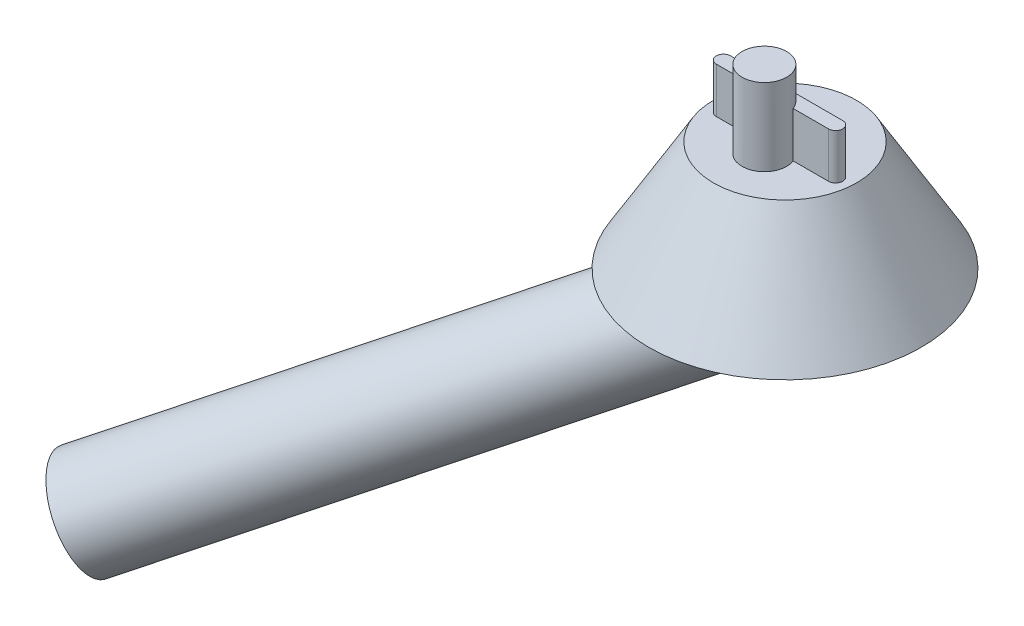
SolidWorks part; units mm, degrees
ref_plane "Front Plane" through (0, 0, 0) normal (0, 0, 1) x (1, 0, 0)
ref_plane "Top Plane" through (0, 0, 0) normal (0, 1, 0) x (1, 0, 0)
ref_plane "Right Plane" through (0, 0, 0) normal (1, 0, 0) x (0, 0, -1)
sketch "Sketch1" plane through (0, 0, 0) normal (1, 0, 0) x (0, 0, -1)
  line L0 (0, 16.5) -> (0, 0)
  line L1 (0, 0) -> (20.5, 0)
  line L3 (0, 16.5) -> (10.75, 16.5)
  line L4 (10.75, 16.5) -> (20.5, 0)
  dimension "D1" = 20.5
  dimension "D2" = 16.5
  dimension "D3" = 10.75
revolve "Revolve1" add sketch "Sketch1" angle 360 about L0
sketch "Sketch4" plane through (0, 0, 0) normal (0, 0, 1) x (1, 0, 0)
  line L0 (886.6963, -4163.2961) -> (885.689, -4179.7653) construction
sketch "Sketch5" plane through (0, 0, 0) normal (0, 1, 0) x (1, 0, 0)
  line L0 (1.4578, -4.8281) -> (-42.8966, 203.8433) construction
  line L1 (-21.6761, -4.9946) -> (-35.2786, -13.4117)
  line L2 (-21.6761, -4.9946) -> (-15.0617, -15.6839)
  line L3 (-35.2786, -13.4117) -> (-28.6643, -24.101)
  line L4 (-15.0617, -15.6839) -> (-28.6643, -24.101)
sketch "Sketch2" plane through (0, 16.5, 0) normal (0, 1, 0) x (1, 0, 0)
  line L0 (0, 0.25) -> (14.4683, 0.25) construction
  line L1 (0, -10.75) -> (20.9731, -10.75) construction
  circle A0 centre (0, -3.1) radius 3.35
  circle A1 centre (0, 0) radius 10.75 construction
  dimension "D1" = 6.7
  dimension "D2" = 11
extrude "Boss-Extrude1" add sketch "Sketch2" along normal blind 11.6
sketch "Sketch3" plane through (0, 16.5, 0) normal (0, 1, 0) x (1, 0, 0)
  line L0 (0, 5.6262) -> (0, -9.5011) construction
  line L1 (-8.425, 0.25) -> (8.425, 0.25)
  line L2 (-8.425, -1.9) -> (8.425, -1.9)
  line L3 (-9.5, -3.8847) -> (-9.5, 4.3231) construction
  line L4 (9.5, 3.6354) -> (9.5, -4.2396) construction
  circle A0 centre (0, -3.1) radius 3.35 construction
  arc A1 (-8.425, 0.25) -> (-8.425, -1.9) centre (-8.425, -0.825) ccw
  arc A2 (8.425, -1.9) -> (8.425, 0.25) centre (8.425, -0.825) ccw
  dimension "D1" = 2.15
  dimension "D2" = 19
extrude "Boss-Extrude2" add sketch "Sketch3" along normal blind 6.82
sketch "Sketch6" plane through (0, 0, 0) normal (0, 0, 1) x (1, 0, 0)
  line L0 (4.5526, -9.8641) -> (25.7779, -21.7742)
  line L2 (25.7779, -21.7742) -> (32.4337, -9.9126)
  line L3 (14.7682, 0) -> (32.4337, -9.9126)
  line L4 (-20.5, 0) -> (20.5, 0) construction
  line L5 (4.5526, -9.8641) -> (-13.0264, 0)
  line L6 (-13.0264, 0) -> (10.0876, 0)
  line L7 (10.0876, 0) -> (14.7682, 0)
  dimension "D1" = 29.298
ref_plane "Plane1" through (-13.6201, -8.9882, 8.4279) normal (-0.7416, -0.4894, 0.4589) x (0.5262, 0, 0.8504)
ref_plane "Plane2" through (-6.2044, -4.0944, 3.8392) normal (-0.7416, -0.4894, 0.4589) x (0.5262, 0, 0.8504)
sketch "Sketch8" plane through (-6.2044, -4.0944, 3.8392) normal (-0.7416, -0.4894, 0.4589) x (0.5262, 0, 0.8504)
  line L0 (0, 7.5586) -> (0, -25.5822) construction
  circle A0 centre (0, -1) radius 7.5
  ellipse E0 centre (0, 0) end of major axis (20.5, 0) minor radius 10.0323 construction
  dimension "D1" = 15
  dimension "D2" = 1
extrude "Boss-Extrude3" add sketch "Sketch8" along normal blind 80 and the other way up to next
